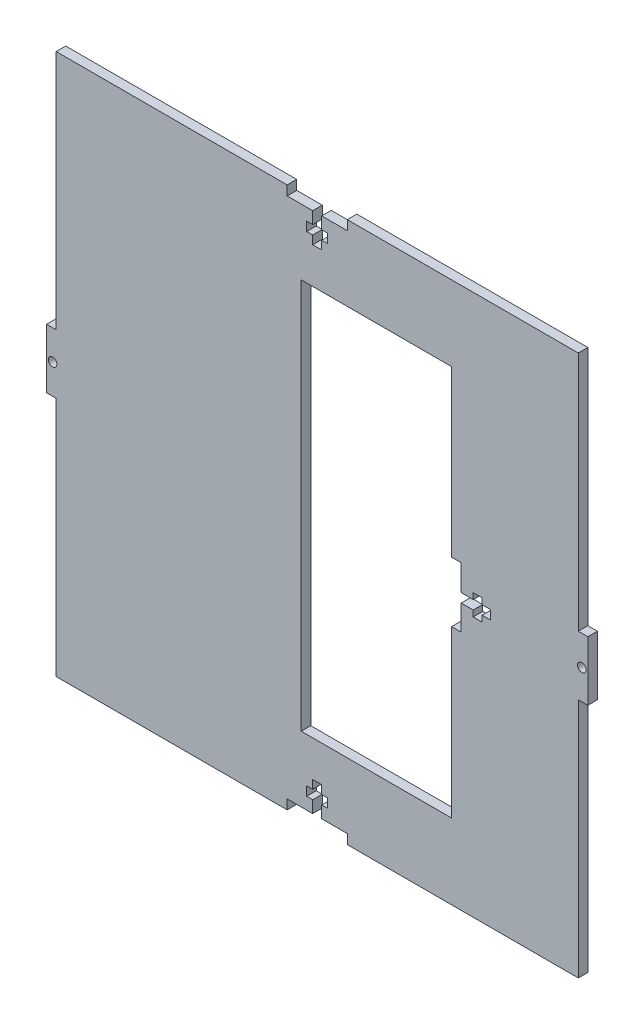
SolidWorks part; units mm, degrees
ref_plane "Front Plane" through (0, 0, 0) normal (0, 0, 1) x (1, 0, 0)
ref_plane "Top Plane" through (0, 0, 0) normal (0, 1, 0) x (1, 0, 0)
ref_plane "Right Plane" through (0, 0, 0) normal (1, 0, 0) x (0, 0, -1)
sketch "Sketch3" plane through (0, 0, 0) normal (0, 0, 1) x (1, 0, 0)
  line L0 (-90, 0) -> (37.62, 0) construction
  line L1 (-90, 90) -> (90, 90)
  line L2 (-90, 90) -> (-90, -90)
  line L3 (-90, -90) -> (90, -90)
  line L4 (90, 90) -> (90, -90)
  line L5 (-90, 0) -> (37.62, 0) construction
  line L6 (0, 90) -> (0, -90) construction
  line L7 (44.6797, -86.695) -> (44.6797, -9.875) construction
  line L8 (-86.564, 0) -> (37.62, 0) construction
  line L9 (44.6797, -65) -> (-5.3203, -65)
  line L10 (44.6797, -65) -> (44.6797, -9.875)
  line L11 (44.6797, 65) -> (-5.3203, 65)
  line L12 (-5.3203, -65) -> (-5.3203, 65)
  line L13 (44.6797, -9.875) -> (47.8597, -9.875)
  line L14 (47.8597, -9.875) -> (47.8597, -1.5)
  line L15 (47.8597, 10.125) -> (44.6797, 10.125)
  line L16 (47.8597, 1.5) -> (51.8597, 1.5)
  line L17 (51.8597, 1.5) -> (51.8597, 3.5)
  line L18 (44.6797, 10.125) -> (44.6797, 65)
  line L19 (51.8597, 3.5) -> (54.8597, 3.5)
  line L20 (40.8, 0) -> (90, 0) construction
  line L21 (40.8, 0) -> (196.9851, 0) construction
  line L22 (54.8597, 3.5) -> (54.8597, 1.5)
  line L23 (54.8597, 1.5) -> (57.6797, 1.5)
  line L24 (57.6797, 1.5) -> (57.6797, -1.5)
  line L25 (54.8597, -1.5) -> (57.6797, -1.5)
  line L26 (54.8597, -3.5) -> (54.8597, -1.5)
  line L27 (51.8597, -3.5) -> (54.8597, -3.5)
  line L28 (51.8597, -1.5) -> (51.8597, -3.5)
  line L29 (47.8597, -1.5) -> (51.8597, -1.5)
  line L30 (47.8597, 1.5) -> (47.8597, 10.125)
  circle A0 centre (-88, 0) radius 1.436 construction
  point P37 (57.6797, 0)
  dimension "D2" = 130
  dimension "D1" = 180
  dimension "D3" = 180
  dimension "D4" = 50
  dimension "D5" = 25
  dimension "D6" = 13
  dimension "D7" = 4
  dimension "D8" = 3
  dimension "D9" = 1.5
  dimension "D10" = 3.5
extrude "Boss-Extrude1" add sketch "Sketch3" along normal blind 3.18
sketch "Sketch4" plane through (0, 0, 3.18) normal (0, 0, 1) x (1, 0, 0)
  line L0 (-90, 90) -> (-90, -90) construction
  line L1 (90, -90) -> (90, 90) construction
  line L2 (-90, 0) -> (90, 0) construction
  line L3 (0.9399, -90) -> (0, -90) construction
  line L4 (90, 90) -> (-90, 90) construction
  line L5 (0, -90) -> (0, 90) construction
  line L6 (1.5, 86.82) -> (10, 86.82)
  line L7 (-10, 90) -> (10, 90)
  line L8 (-10, 90) -> (-10, 86.82)
  line L9 (-10, 86.82) -> (-1.5, 86.82)
  line L10 (10, 90) -> (10, 86.82)
  line L11 (-3.5, 82.82) -> (-1.5, 82.82)
  line L12 (-3.5, 82.82) -> (-3.5, 79.82)
  line L13 (-3.5, 79.82) -> (-1.5, 79.82)
  line L14 (3.5, 82.82) -> (3.5, 79.82)
  line L15 (1.5, 82.82) -> (3.5, 82.82)
  line L16 (-1.5, 86.82) -> (-1.5, 82.82)
  line L17 (-1.5, 77) -> (1.5, 77)
  line L18 (1.5, 86.82) -> (1.5, 82.82)
  line L19 (-90, -90) -> (90, -90) construction
  line L20 (1.5, 79.82) -> (3.5, 79.82)
  line L21 (-1.5, 79.82) -> (-1.5, 77)
  line L22 (1.5, 79.82) -> (1.5, 77)
  line L23 (1.5, -79.82) -> (1.5, -77)
  line L24 (-1.5, -79.82) -> (-1.5, -77)
  line L25 (1.5, -79.82) -> (3.5, -79.82)
  line L26 (1.5, -86.82) -> (1.5, -82.82)
  line L27 (-1.5, -77) -> (1.5, -77)
  line L28 (-1.5, -86.82) -> (-1.5, -82.82)
  line L29 (1.5, -82.82) -> (3.5, -82.82)
  line L30 (3.5, -82.82) -> (3.5, -79.82)
  line L31 (-3.5, -79.82) -> (-1.5, -79.82)
  line L32 (-3.5, -82.82) -> (-3.5, -79.82)
  line L33 (-3.5, -82.82) -> (-1.5, -82.82)
  line L34 (10, -90) -> (10, -86.82)
  line L35 (-10, -86.82) -> (-1.5, -86.82)
  line L36 (-10, -90) -> (-10, -86.82)
  line L37 (-10, -90) -> (10, -90)
  line L38 (1.5, -86.82) -> (10, -86.82)
  dimension "D1" = 20
  dimension "D2" = 3.18
  dimension "D3" = 4
  dimension "D4" = 3
  dimension "D5" = 3
  dimension "D6" = 13
  dimension "D7" = 7
sketch "Sketch5" plane through (0, 0, 3.18) normal (0, 0, 1) x (1, 0, 0)
  line L0 (-90, 0) -> (90, 0) construction
  line L1 (-90, 90) -> (-86.82, 90)
  line L2 (-90, 90) -> (-90, 9.875)
  line L3 (-90, 9.875) -> (-86.82, 9.875)
  line L4 (-86.82, 90) -> (-86.82, 9.875)
  line L5 (-90, -90) -> (-86.82, -90)
  line L6 (-90, -90) -> (-90, -9.875)
  line L7 (-90, -9.875) -> (-86.82, -9.875)
  line L8 (-86.82, -90) -> (-86.82, -9.875)
  line L9 (-90, 90) -> (-90, -90) construction
  line L10 (0, 90) -> (0, -90) construction
  line L11 (86.82, -90) -> (86.82, -9.875)
  line L12 (90, -9.875) -> (86.82, -9.875)
  line L13 (90, -90) -> (90, -9.875)
  line L14 (90, -90) -> (86.82, -90)
  line L15 (86.82, 90) -> (86.82, 9.875)
  line L16 (90, 9.875) -> (86.82, 9.875)
  line L17 (90, 90) -> (90, 9.875)
  line L18 (90, 90) -> (86.82, 90)
  circle A0 centre (-88, 0) radius 1.436
  circle A1 centre (88, 0) radius 1.436
  dimension "D4" = 2.872
  dimension "D5" = 2
  dimension "D1" = 3.18
  dimension "D2" = 3.18
  dimension "D3" = 19.75
extrude "Cut-Extrude1" cut sketch "Sketch4" against normal through all
extrude "Cut-Extrude2" cut sketch "Sketch5" against normal through all
